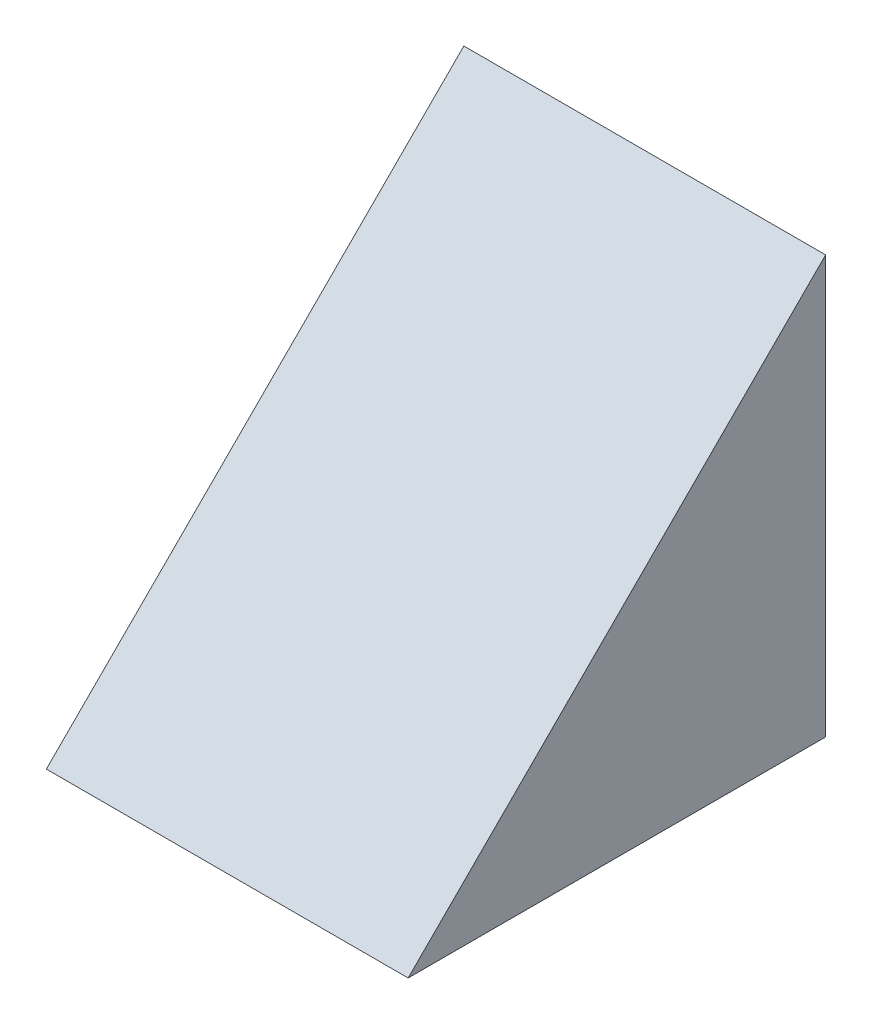
SolidWorks part; units mm, degrees
ref_plane "Front Plane" through (0, 0, 0) normal (0, 0, 1) x (1, 0, 0)
ref_plane "Top Plane" through (0, 0, 0) normal (0, 1, 0) x (1, 0, 0)
ref_plane "Right Plane" through (0, 0, 0) normal (1, 0, 0) x (0, 0, -1)
sketch "Sketch1" plane through (-5.958, 0, 0) normal (1, 0, 0) x (0, 0, -1)
  line L0 (-7.303, -51.9052) -> (-7.303, -21.9052)
  line L1 (-7.303, 48.0948) -> (-7.303, -51.9052) construction
  line L2 (-7.303, -21.9052) -> (-37.303, -51.9052)
  line L3 (-95.953, -51.9052) -> (-0.953, -51.9052) construction
  line L4 (-37.303, -51.9052) -> (-7.303, -51.9052)
  dimension "D1" = 30
  dimension "D2" = 30
sketch "Sketch2" plane through (-5.958, 0, 0) normal (1, 0, 0) x (0, 0, -1)
  line L0 (-7.303, -51.9052) -> (-7.303, -21.9052)
  line L1 (-7.303, 48.0948) -> (-7.303, -51.9052) construction
  line L2 (-7.303, -21.9052) -> (-37.303, -51.9052)
  line L3 (-95.953, -51.9052) -> (-0.953, -51.9052) construction
  line L4 (-37.303, -51.9052) -> (-7.303, -51.9052)
  dimension "D1" = 30
  dimension "D2" = 30
extrude "Boss-Extrude2" add sketch "Sketch2" against normal blind 26
